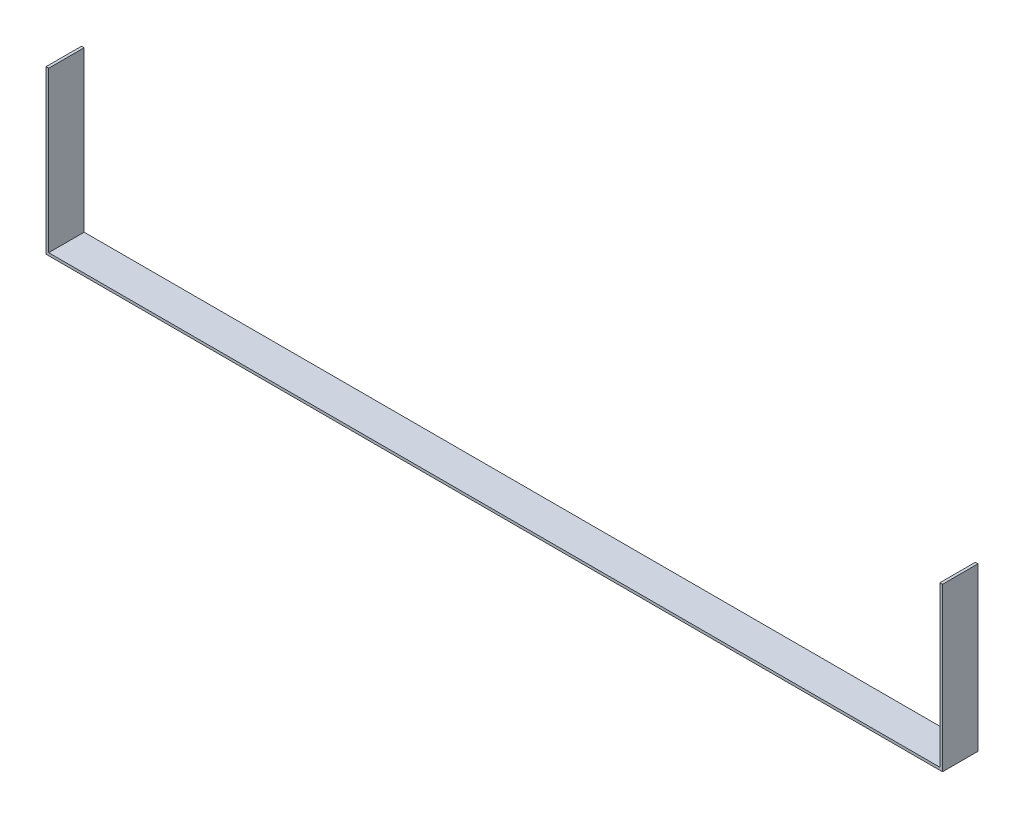
SolidWorks part; units mm, degrees
ref_plane "Front" through (0, 0, 0) normal (0, 0, 1) x (1, 0, 0)
ref_plane "Top" through (0, 0, 0) normal (0, 1, 0) x (1, 0, 0)
ref_plane "Right" through (0, 0, 0) normal (1, 0, 0) x (0, 0, -1)
sketch "Sketch1" plane through (0, 0, 0) normal (0, 0, 1) x (1, 0, 0)
  line L0 (-251, 90) -> (-251, 0)
  line L1 (-251, 0) -> (251, 0)
  line L2 (251, 0) -> (251, 90)
  line L3 (-252.5, 90) -> (-252.5, -1.5)
  line L4 (-252.5, -1.5) -> (252.5, -1.5)
  line L5 (252.5, -1.5) -> (252.5, 90)
  line L6 (-251, 90) -> (-252.5, 90)
  line L7 (251, 90) -> (252.5, 90)
  point P2 (0, 0)
  dimension "D1" = 502
  dimension "D2" = 90
  dimension "D3" = 90
  dimension "D4" = 1.5
extrude "Boss-Extrude1" add sketch "Sketch1" along normal blind 20
